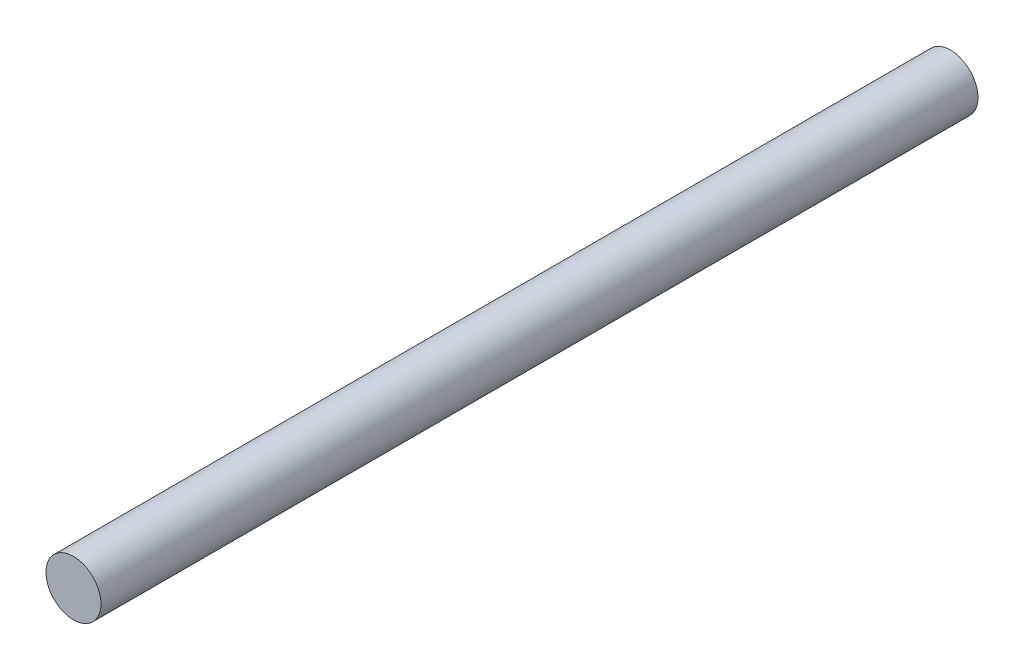
SolidWorks part; units mm, degrees
ref_plane "Front Plane" through (0, 0, 0) normal (0, 0, 1) x (1, 0, 0)
ref_plane "Top Plane" through (0, 0, 0) normal (0, 1, 0) x (1, 0, 0)
ref_plane "Right Plane" through (0, 0, 0) normal (1, 0, 0) x (0, 0, -1)
sketch "Sketch1" plane through (0, 0, 0) normal (0, 0, 1) x (1, 0, 0)
  circle A0 centre (0, 0) radius 2.5
  dimension "D1" = 5
extrude "Boss-Extrude1" add sketch "Sketch1" along normal blind 79.72
